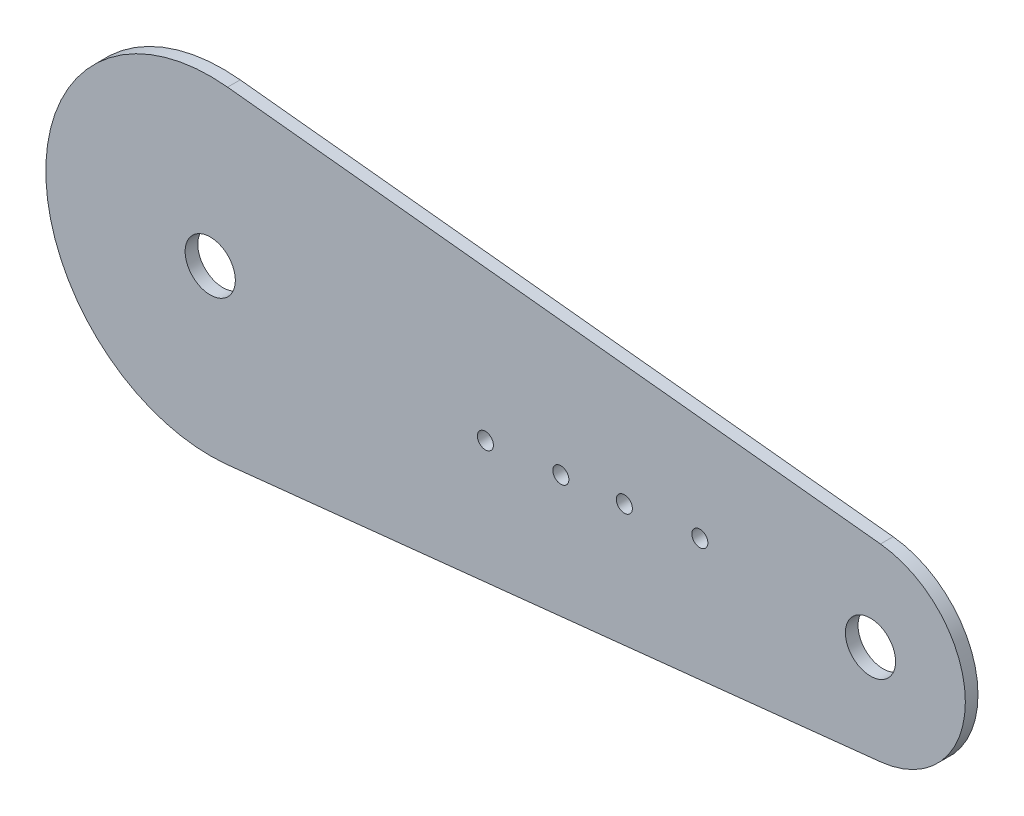
SolidWorks part; units mm, degrees
ref_plane "Alzado" through (0, 0, 0) normal (0, 0, 1) x (1, 0, 0)
ref_plane "Planta" through (0, 0, 0) normal (0, 1, 0) x (1, 0, 0)
ref_plane "Vista lateral" through (0, 0, 0) normal (1, 0, 0) x (0, 0, -1)
sketch "Croquis1" plane through (0, 0, 0) normal (0, 0, 1) x (1, 0, 0)
  line L1 (130.5, 0) -> (0, 0) construction
  line L2 (-130.5, 0) -> (0, 0) construction
  line L3 (-123.6513, 64.6382) -> (134.4511, 37.2913)
  line L4 (134.4511, -37.2913) -> (-123.6513, -64.6382)
  arc A0 (-123.6513, 64.6382) -> (-123.6513, -64.6382) centre (-130.5, 0) ccw
  arc A1 (134.4511, -37.2913) -> (134.4511, 37.2913) centre (130.5, 0) ccw
  circle A2 centre (63.0361, 3.5068) radius 3.175 construction
  circle A3 centre (33.2002, 0.3742) radius 3.175 construction
  circle A4 centre (-21.7378, -5.3941) radius 3.175 construction
  circle A5 centre (8.0981, -2.2614) radius 3.175 construction
  circle A6 centre (63.0361, 3.5068) radius 3.175
  circle A7 centre (33.2002, 0.3742) radius 3.175
  circle A8 centre (-21.7378, -5.3941) radius 3.175
  circle A9 centre (8.0981, -2.2614) radius 3.175
  dimension "D2" = 75
  dimension "D3" = 130
  dimension "D1" = 261
extrude "Saliente-Extruir1" add sketch "Croquis1" along normal mid plane 5
sketch "Croquis2" plane through (0, 0, 2.5) normal (0, 0, 1) x (1, 0, 0)
  circle A0 centre (-130.5, 0) radius 9.9219
  circle A1 centre (130.5, 0) radius 9.9219
  dimension "D1" = 19.8438
extrude "Cortar-Extruir1" cut sketch "Croquis2" against normal blind 10
